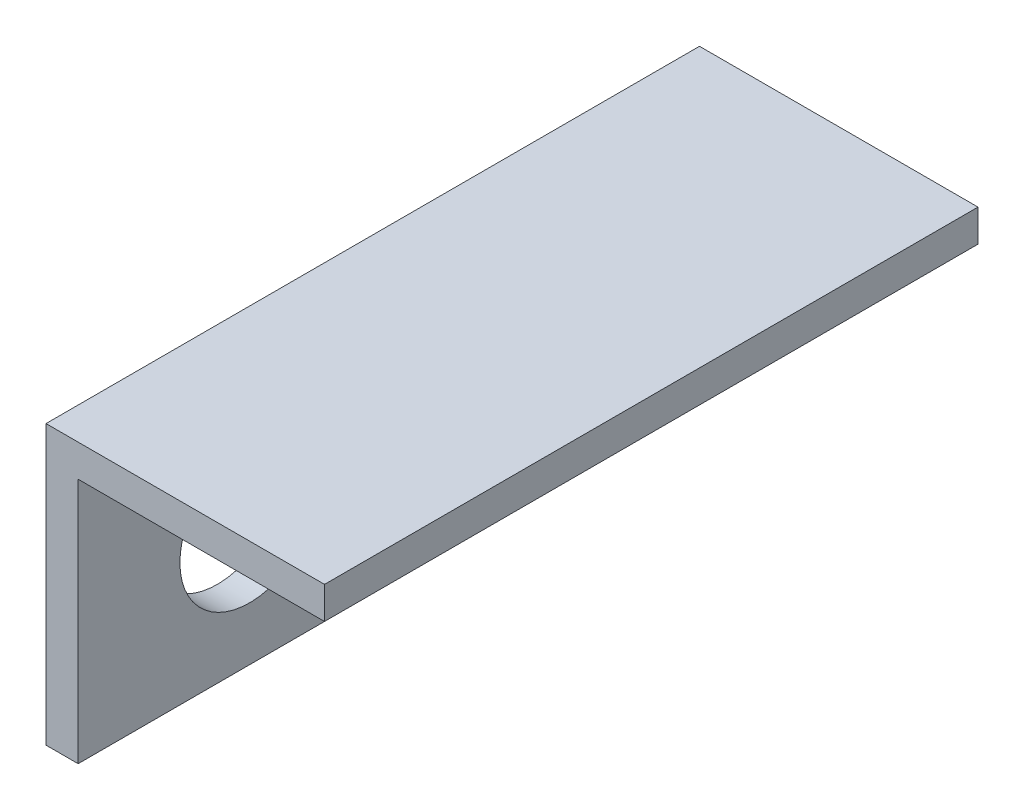
SolidWorks part; units mm, degrees
material "1060 Alloy"
ref_plane "Front Plane" through (0, 0, 0) normal (0, 0, 1) x (1, 0, 0)
ref_plane "Top Plane" through (0, 0, 0) normal (0, 1, 0) x (1, 0, 0)
ref_plane "Right Plane" through (0, 0, 0) normal (1, 0, 0) x (0, 0, -1)
sketch "Sketch1" plane through (0, 0, 0) normal (1, 0, 0) x (0, 0, -1)
  line L1 (-30.5, 13) -> (30.5, 13)
  line L2 (-30.5, 13) -> (-30.5, -13)
  line L3 (-30.5, -13) -> (30.5, -13)
  line L4 (30.5, 13) -> (30.5, -13)
  line L5 (-30.5, 13) -> (30.5, -13) construction
  line L6 (-30.5, -13) -> (30.5, 13) construction
  point P0 (0, 0)
  dimension "D1" = 26
  dimension "D2" = 61
extrude "Boss-Extrude1" add sketch "Sketch1" along normal blind 3
sketch "Sketch3" plane through (0, 0, 0) normal (1, 0, 0) x (0, 0, -1)
  line L0 (-30.5, 13) -> (-30.5, -13) construction
  line L1 (30.5, 13) -> (-30.5, 13)
  line L2 (30.5, 13) -> (30.5, 10)
  line L3 (30.5, 10) -> (-30.5, 10)
  line L4 (-30.5, 13) -> (-30.5, 10)
  dimension "D1" = 3
extrude "Boss-Extrude2" add sketch "Sketch3" along normal blind 26
sketch "Sketch4" plane through (0, 0, 0) normal (1, 0, 0) x (0, 0, -1)
  line L0 (-30.5, -13) -> (30.5, -13) construction
  line L1 (30.5, -13) -> (30.5, 13) construction
  line L2 (-30.5, 13) -> (-30.5, -13) construction
  circle A0 centre (10.5, -1.5) radius 2.5
  circle A1 centre (-14.5, -1.5) radius 6.5
  dimension "D1" = 5
  dimension "D2" = 13
  dimension "D5" = 16
  dimension "D3" = 11.5
  dimension "D4" = 20
extrude "Cut-Extrude1" cut sketch "Sketch4" along normal through all
sketch "Sketch5" plane through (0, 0, 0) normal (-1, 0, 0) x (0, 0, 1)
  text T0 "BATT\r\nOFF\r\nWALL"
extrude "Cut-Extrude2" cut sketch "Sketch5" against normal blind 0.5
sketch "Sketch6" plane through (0, 0, 0) normal (1, 0, 0) x (0, 0, -1)
  text T0 "0"
extrude "Cut-Extrude3" cut sketch "Sketch6" along normal blind 0.5
sketch "Sketch7" plane through (0, 0, 0) normal (1, 0, 0) x (0, 0, -1)
  text T0 "1"
extrude "Cut-Extrude4" cut sketch "Sketch7" along normal blind 0.5
